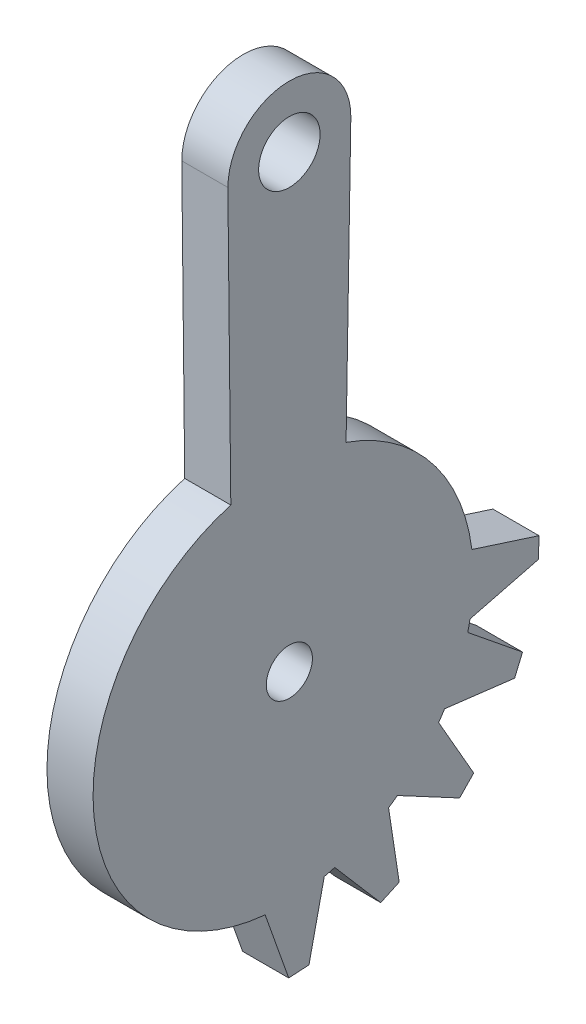
SolidWorks part; units mm, degrees
ref_plane "正面" through (0, 0, 0) normal (0, 0, 1) x (1, 0, 0)
ref_plane "平面" through (0, 0, 0) normal (0, 1, 0) x (1, 0, 0)
ref_plane "右側面" through (0, 0, 0) normal (1, 0, 0) x (0, 0, -1)
sketch "ｽｹｯﾁ1" plane through (0, 0, 0) normal (1, 0, 0) x (0, 0, -1)
  line L0 (60.8916, -3.3645) -> (63.8673, -6.8581)
  line L68 (60.8916, -3.3645) -> (61.6212, -2.2646)
  line L70 (64.9744, 1.1906) -> (66.052, 1.9527)
  line L71 (66.052, 1.9527) -> (69.6331, -0.9171)
  line L72 (64.9744, 1.1906) -> (66.4871, -3.1421)
  line L73 (70.4269, 3.9632) -> (71.707, 4.2846)
  line L74 (71.707, 4.2846) -> (74.0097, 0.3149)
  line L75 (70.4269, 3.9632) -> (70.2723, -0.6234)
  line L76 (76.5128, 4.5789) -> (77.8226, 4.4161)
  line L77 (77.8226, 4.4161) -> (78.5357, -0.1173)
  line L78 (76.5128, 4.5789) -> (74.7118, 0.3579)
  line L79 (82.4101, 2.9545) -> (83.5727, 2.3296)
  line L80 (83.5727, 2.3296) -> (82.6, -2.1553)
  line L81 (82.4101, 2.9545) -> (79.2059, -0.3308)
  line L82 (87.3225, -0.6905) -> (88.1807, -1.6932)
  line L83 (88.1807, -1.6932) -> (85.6536, -5.5239)
  line L84 (87.3225, -0.6905) -> (83.1478, -2.5965)
  line L85 (90.5863, -5.8639) -> (91.0244, -7.109)
  line L86 (91.0244, -7.109) -> (87.2842, -9.7681)
  line L87 (90.5863, -5.8639) -> (86.0051, -6.1332)
  line L88 (91.7609, -11.8671) -> (91.7197, -13.1863)
  line L89 (91.7197, -13.1863) -> (87.2714, -14.3147)
  line L90 (91.7609, -11.8671) -> (87.3918, -10.4632)
  line L91 (90.6876, -17.8891) -> (90.1727, -19.1044)
  line L92 (90.1727, -19.1044) -> (85.6171, -18.5497)
  line L93 (90.6876, -17.8891) -> (87.1207, -15.0017)
  line L94 (87.5114, -23.1168) -> (86.5922, -24.064)
  line L95 (86.5922, -24.064) -> (82.5447, -21.9011)
  line L96 (87.5114, -23.1168) -> (85.2284, -19.1359)
  line L97 (82.6612, -26.8441) -> (81.4619, -27.3952)
  line L98 (81.4619, -27.3952) -> (78.4691, -23.9163)
  line L99 (82.6612, -26.8441) -> (81.9704, -22.3072)
  line L100 (76.7921, -28.5676) -> (75.4747, -28.6483)
  line L101 (75.4747, -28.6483) -> (73.9407, -24.3231)
  line L102 (76.7921, -28.5676) -> (77.7868, -24.0876)
  line L103 (70.6967, -28.0545) -> (69.4391, -27.6539)
  line L104 (69.4391, -27.6539) -> (69.5711, -23.0666)
  line L105 (70.6967, -28.0545) -> (73.2426, -24.2364)
  line L106 (65.1982, -25.3742) -> (64.1703, -24.5463)
  line L107 (64.1703, -24.5463) -> (65.9505, -20.3165)
  line L108 (65.1982, -25.3742) -> (68.9515, -22.7336)
  line L109 (61.0393, -20.8886) -> (60.3799, -19.7453)
  line L110 (60.3799, -19.7453) -> (63.5678, -16.4442)
  line L111 (61.0393, -20.8886) -> (65.4931, -19.7821)
  line L112 (58.7816, -15.2035) -> (58.5797, -13.8992)
  line L113 (58.5797, -13.8992) -> (62.7449, -11.9727)
  line L114 (58.7816, -15.2035) -> (63.3343, -15.7807)
  line L115 (58.7301, -9.0868) -> (59.013, -7.7976)
  line L116 (59.013, -7.7976) -> (63.5929, -7.5058)
  line L117 (58.7301, -9.0868) -> (62.7669, -11.2696)
  line L119 (71.5164, 17.8753) -> (71.707, -0.1146)
  line L121 (79.5164, 17.8753) -> (79.2059, -0.3308)
  circle A11 centre (75.5164, -11.4047) radius 1.5
  circle A12 centre (75.1167, -12.0073) radius 12.3718
  circle A16 centre (75.5164, 17.8753) radius 2
  circle A17 centre (75.5164, 17.8753) radius 4
  point P131 (61.2564, -2.8145)
  point P137 (65.5132, 1.5716)
  point P142 (71.067, 4.1239)
  point P147 (77.1677, 4.4975)
  point P152 (82.9914, 2.6421)
  point P157 (87.7516, -1.1918)
  point P162 (90.8054, -6.4864)
  point P167 (91.7403, -12.5267)
  point P172 (90.4302, -18.4968)
  point P177 (87.0518, -23.5904)
  point P182 (82.0616, -27.1197)
  point P187 (76.1334, -28.608)
  point P192 (70.0679, -27.8542)
  point P197 (64.6842, -24.9603)
  point P202 (60.7096, -20.3169)
  point P207 (58.6807, -14.5514)
  point P212 (58.8715, -8.4422)
  point P213 (75.1167, -12.0073)
extrude "ﾎﾞｽ - 押し出し2" add sketch "ｽｹｯﾁ1" along normal blind 3 contours A17 L119 L73 L74 A12 L78 L76 L77 L121 | L121 A17 L119 A16 | A12 A11 | A12 L74 L73 L119 | A12 L77 L76 L78 | A12 L89 L88 L90 | A12 L92 L91 L93 | A12 L95 L94 L96 | A12 L98 L97 L99 | A12 L101 L100 L102
